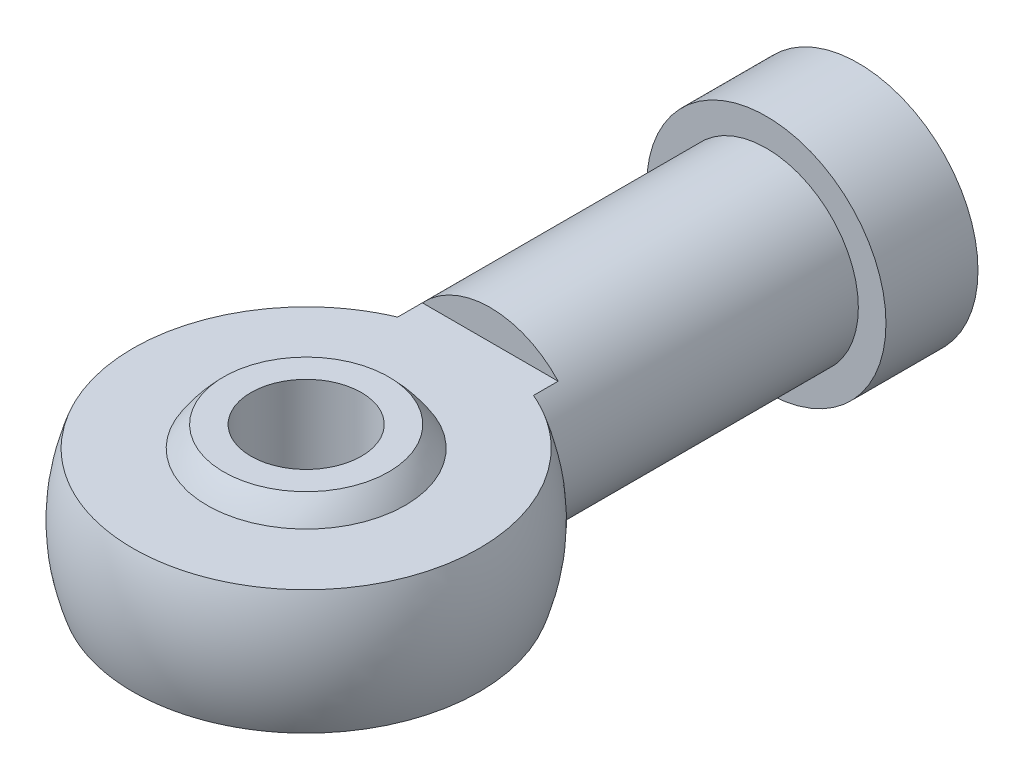
SolidWorks part; units mm, degrees
material "6061 合金"
ref_plane "前视基准面" through (0, 0, 0) normal (0, 0, 1) x (1, 0, 0)
ref_plane "上视基准面" through (0, 0, 0) normal (0, 1, 0) x (1, 0, 0)
ref_plane "右视基准面" through (0, 0, 0) normal (1, 0, 0) x (0, 0, -1)
sketch "草图3" plane through (0, 0, 0) normal (0, 0, 1) x (1, 0, 0)
  circle A0 centre (0, 0) radius 6.5
  dimension "D1" = 13
extrude "凸台-拉伸1" add sketch "草图3" along normal blind 5
sketch "草图4" plane through (0, 0, 5) normal (0, 0, 1) x (1, 0, 0)
  circle A0 centre (0, 0) radius 5
  dimension "D1" = 10
extrude "凸台-拉伸2" add sketch "草图4" along normal blind 20
sketch "草图5" plane through (0, 0, 0) normal (0, 1, 0) x (1, 0, 0)
  line L0 (0, 0) -> (0, -30) construction
  line L1 (0, -20) -> (0, -40)
  arc A0 (0, -20) -> (0, -40) centre (0, -30) ccw
  dimension "D1" = 30
  dimension "D2" = 20
revolve "旋转4" add sketch "草图5" angle 360 about L0
ref_plane "基准面1" through (0, 0, 20) normal (0, 0, 1) x (1, 0, 0)
sketch "草图6" plane through (0, 0, 20) normal (0, 0, 1) x (1, 0, 0)
  line L1 (12.5, 12.5) -> (-12.5, 12.5)
  line L2 (12.5, 12.5) -> (12.5, -12.5)
  line L3 (12.5, -12.5) -> (-12.5, -12.5)
  line L4 (-12.5, 12.5) -> (-12.5, -12.5)
  line L5 (12.5, 12.5) -> (-12.5, -12.5) construction
  line L6 (12.5, -12.5) -> (-12.5, 12.5) construction
  line L7 (12, 3.375) -> (-12, 3.375)
  line L8 (12, 3.375) -> (12, -3.375)
  line L9 (12, -3.375) -> (-12, -3.375)
  line L10 (-12, 3.375) -> (-12, -3.375)
  line L11 (12, 3.375) -> (-12, -3.375) construction
  line L12 (12, -3.375) -> (-12, 3.375) construction
  point P0 (0, 0)
  point P5 (0, 0)
  dimension "D1" = 25
  dimension "D2" = 6.75
  dimension "D3" = 24
extrude "切除-拉伸1" cut sketch "草图6" along normal blind 25
ref_plane "基准面2" through (0, 0, 0) normal (0, 1, 0) x (1, 0, 0)
sketch "草图8" plane through (0, 0, 0) normal (0, 1, 0) x (1, 0, 0)
  line L0 (-10, -30) -> (10, -30) construction
  line L4 (-6.35, -30) -> (6.35, -30)
  arc A0 (-5, -21.3397) -> (5, -21.3397) centre (0, -30) ccw construction
  arc A4 (-3.6891, -21.3397) -> (3.6891, -21.3397) centre (0, -30) ccw construction
  arc A5 (-3.6891, -21.3397) -> (3.6891, -21.3397) centre (0, -30) ccw
  arc A6 (-6.35, -30) -> (6.35, -30) centre (0, -30) ccw
  dimension "D1" = 12.7
revolve "旋转5" add sketch "草图8" angle 360 about L0
sketch "草图10" plane through (0, 0, 0) normal (0, 1, 0) x (1, 0, 0)
  circle A0 centre (0, -30) radius 5.3788 construction
  circle A1 centre (0, -30) radius 5.3788
  circle A2 centre (0, -30) radius 3
  dimension "D1" = 6
extrude "切除-拉伸3" cut sketch "草图10" against normal through all and the other way through all contours A2
sketch "草图13" plane through (0, 0, 0) normal (0, 0, -1) x (-1, 0, 0)
  line L0 (0, 6.5) -> (0, -6.5) construction
  circle A0 centre (0, 0) radius 6.5 construction
  point P5 (0, 0)
hole_wizard "M6 螺纹孔1" positions "3D草图4" profile "草图15" tap size "M6" standard "ISO"
sketch3d "3D草图4"
  line L0 (0, 6.5, 0) -> (0, -6.5, 0) construction
  point P0 (0, 0, 0)
  point P3 (0, 0, 0)
  point P7 (0, 0, 0)
sketch "草图15" plane through (0, 0, 0) normal (1, 0, 0) x (0, 1, 0)
  line L0 (0, 0) -> (0, 16.5022)
  line L1 (0, 16.5022) -> (2.5, 15)
  line L2 (2.5, 15) -> (2.5, 0.525)
  line L3 (2.5, 0.525) -> (3.025, 0)
  line L5 (3.025, 0) -> (0, 0)
  line L6 (-2.5, 0.525) -> (-3.025, 0) construction
  line L10 (0, 16.5022) -> (-2.5, 15) construction
  line L11 (0, -6.35) -> (0, 107.95) construction
  dimension "螺纹孔钻头直径" = 5
  dimension "螺纹孔钻头深度" = 15
  dimension "近端锥形沉头孔直径" = 6.05
  dimension "近端锥形沉头孔角度" = 90
  dimension "导头角度" = 118
cosmetic thread "孔螺蚊线1" parameters "D1"=12, "D2"=6
cosmetic thread "孔螺蚊线2" parameters "D1"=12, "D2"=6
cosmetic thread "孔螺蚊线3" parameters "D1"=12, "D2"=6
sketch "草图16" plane through (0, 0, 20) normal (0, 0, 1) x (1, 0, 0)
  line L1 (12.5, 4.5) -> (-12.5, 4.5)
  line L2 (12.5, 4.5) -> (12.5, -4.5)
  line L3 (12.5, -4.5) -> (-12.5, -4.5)
  line L4 (-12.5, 4.5) -> (-12.5, -4.5)
  line L5 (12.5, 4.5) -> (-12.5, -4.5) construction
  line L6 (12.5, -4.5) -> (-12.5, 4.5) construction
  circle A0 centre (0, 0) radius 20
  point P0 (0, 0)
  dimension "D3" = 40
  dimension "D1" = 9
  dimension "D2" = 25
extrude "切除-拉伸4" cut sketch "草图16" along normal through all
